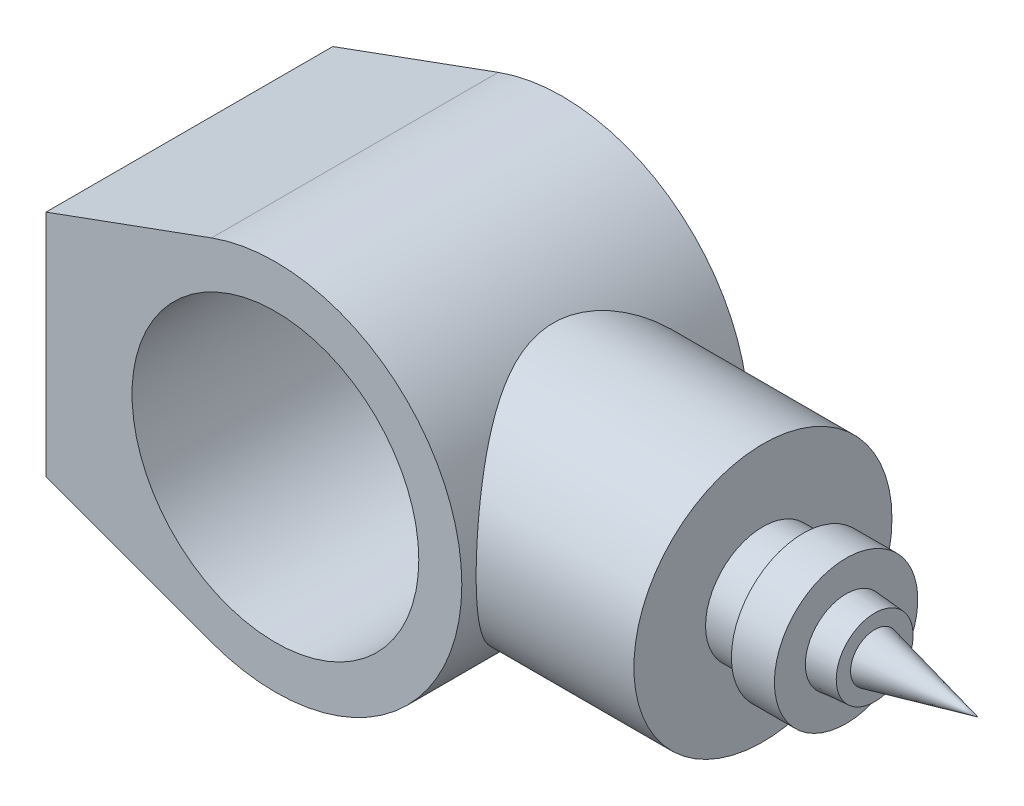
SolidWorks part; units mm, degrees
ref_plane "Front Plane" through (0, 0, 0) normal (0, 0, 1) x (1, 0, 0)
ref_plane "Top Plane" through (0, 0, 0) normal (0, 1, 0) x (1, 0, 0)
ref_plane "Right Plane" through (0, 0, 0) normal (1, 0, 0) x (0, 0, -1)
sketch "Sketch1" plane through (0, 0, 0) normal (0, 0, 1) x (1, 0, 0)
  line L0 (-80, -40) -> (-80, 40)
  line L1 (-80, 40) -> (-22.2817, 61.0617)
  line L2 (-80, -40) -> (-22.2817, -61.0617)
  arc A0 (-22.2817, -61.0617) -> (-22.2817, 61.0617) centre (0, 0) ccw
  circle A1 centre (0, 0) radius 50
  point P7 (-80, 0)
  dimension "D1" = 130
  dimension "D2" = 100
  dimension "D3" = 80
  dimension "D4" = 80
extrude "Boss-Extrude1" add sketch "Sketch1" along normal mid plane 100
ref_plane "Plane1" through (120, 0, 0) normal (1, 0, 0) x (0, 0, -1)
sketch "Sketch2" plane through (120, 0, 0) normal (1, 0, 0) x (0, 0, -1)
  circle A0 centre (0, 0) radius 45
  dimension "D1" = 90
extrude "Boss-Extrude2" add sketch "Sketch2" against normal up to next
sketch "Sketch3" plane through (0, 0, 0) normal (0, 0, 1) x (1, 0, 0)
  line L0 (0, 0) -> (285.9032, 0) construction
  line L1 (120, 0) -> (120, -20)
  line L2 (120, -45) -> (120, 45) construction
  line L3 (120, -20) -> (134, -20)
  line L4 (134, -20) -> (134, -25)
  line L5 (134, -25) -> (149, -25)
  line L6 (149, -25) -> (149, -14.2079)
  line L7 (149, -14.2079) -> (158.9679, -13.4078)
  line L8 (158.9679, -13.4078) -> (158.9679, -8.4078)
  line L9 (158.9679, -8.4078) -> (195, 0)
  line L10 (195, 0) -> (120, 0)
  dimension "D1" = 20
  dimension "D2" = 14
  dimension "D3" = 5
  dimension "D4" = 15
  dimension "D5" = 10
  dimension "D6" = 37
  dimension "D7" = 5
  dimension "D8" = 75
revolve "Revolve1" add sketch "Sketch3" angle 360 about L0
